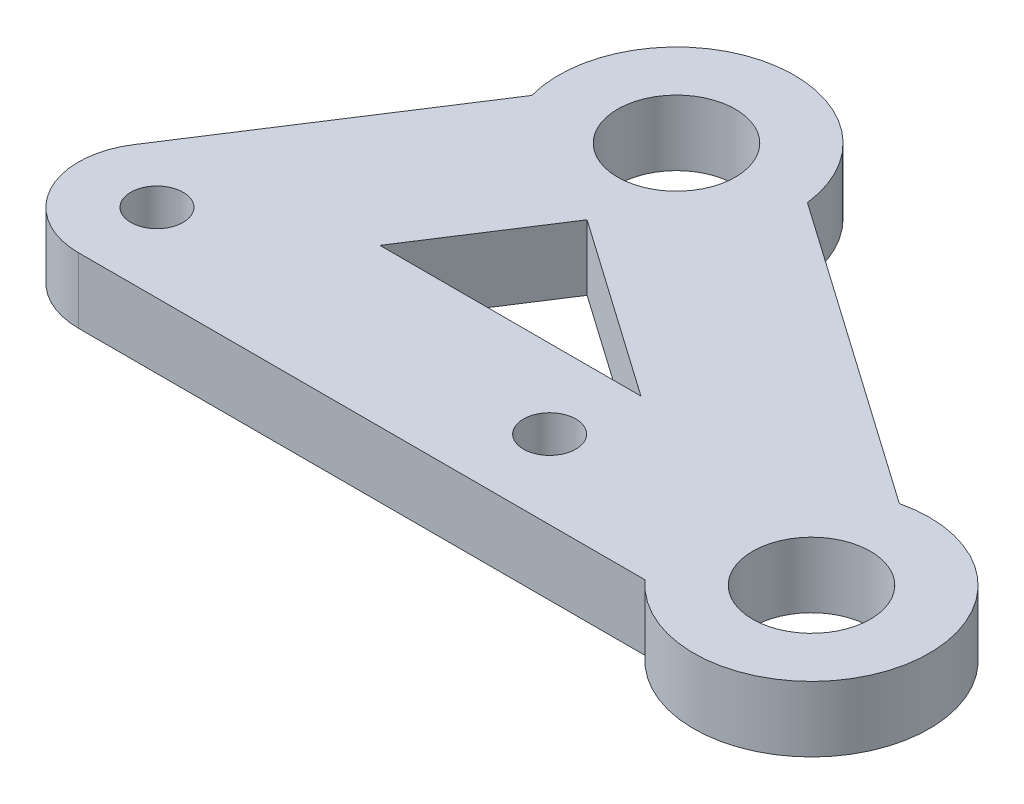
SolidWorks part; units mm, degrees
ref_plane "前视基准面" through (0, 0, 0) normal (0, 0, 1) x (1, 0, 0)
ref_plane "上视基准面" through (0, 0, 0) normal (0, 1, 0) x (1, 0, 0)
ref_plane "右视基准面" through (0, 0, 0) normal (1, 0, 0) x (0, 0, -1)
sketch "草图1" plane through (0, 0, 0) normal (0, 1, 0) x (1, 0, 0)
  line L0 (-11.3488, 7.2699) -> (2.372, -2.3375)
  line L1 (-11.3488, 7.2699) -> (-17.5689, -2.3375)
  line L2 (2.372, -2.3375) -> (-17.5689, -2.3375)
  line L4 (1.3989, -8.3375) -> (-0.6011, -8.3375)
  line L6 (-21.6863, 13.3833) -> (-33.6377, -5.0767)
  line L7 (14.6934, -14.3375) -> (-28.6011, -14.3375)
  line L8 (-4.0675, 16.8208) -> (19.348, 0.4251)
  line L9 (-14.6592, 24.2372) -> (-39.6334, -14.3375) construction
  line L10 (-14.6592, 24.2372) -> (40.4311, -14.3375) construction
  line L11 (40.4311, -14.3375) -> (-39.6334, -14.3375) construction
  line L12 (-13.004, 15.7535) -> (21.4016, -8.3375) construction
  line L13 (21.4016, -8.3375) -> (-28.6011, -8.3375) construction
  line L15 (-13.004, 15.7535) -> (-28.6011, -8.3375) construction
  arc A0 (14.6934, -14.3375) -> (19.348, 0.4251) centre (21.4016, -8.3375) ccw
  circle A1 centre (21.4016, -8.3375) radius 4.5
  arc A2 (-28.6011, -14.3375) -> (-33.6377, -5.0767) centre (-28.6011, -8.3375) cw
  circle A3 centre (-28.6011, -8.3375) radius 2
  arc A4 (-11.6131, 6.8617) -> (-10.9504, 6.9909) centre (-13.004, 15.7535) ccw
  circle A5 centre (-13.004, 15.7535) radius 4.5
  arc A6 (-4.0675, 16.8208) -> (-21.6863, 13.3833) centre (-13.004, 15.7535) ccw
  circle A7 centre (1.3989, -8.3375) radius 2
  dimension "D1" = 16.75
  dimension "D2" = 35
  dimension "D3" = 57.08
  dimension "D4" = 6
extrude "凸台-拉伸1" add sketch "草图1" along normal blind 5 contours L8 A6 L6 A2 L7 A0 A7 L0 L2 L1 A1 A3 A5
